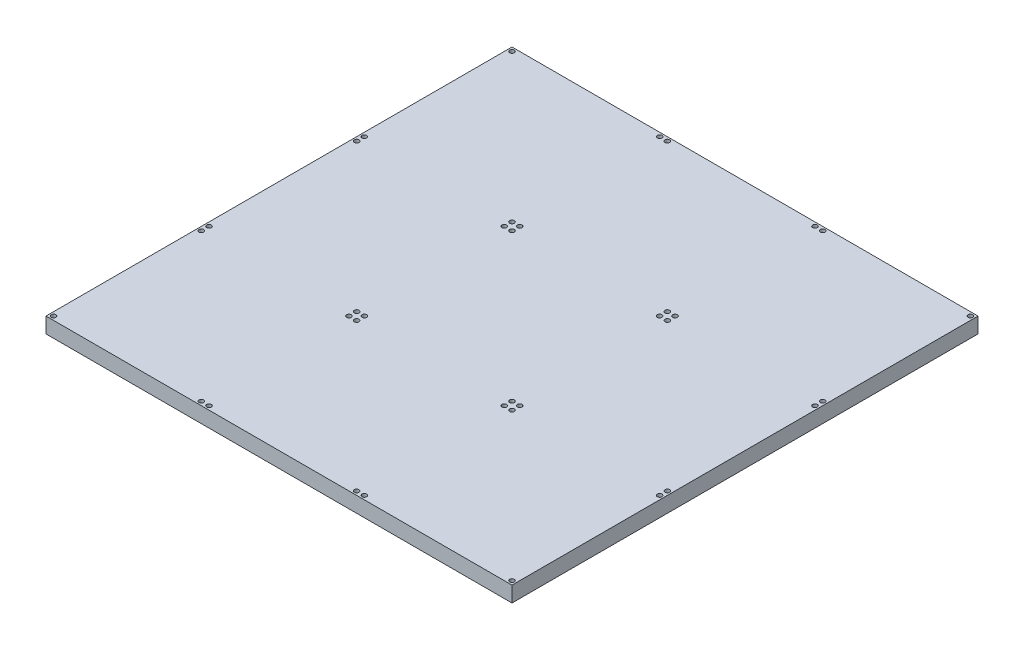
SolidWorks part; units mm, degrees
ref_plane "Front Plane" through (0, 0, 0) normal (0, 0, 1) x (1, 0, 0)
ref_plane "Top Plane" through (0, 0, 0) normal (0, 1, 0) x (1, 0, 0)
ref_plane "Right Plane" through (0, 0, 0) normal (1, 0, 0) x (0, 0, -1)
sketch "Sketch1" plane through (0, 0, 0) normal (0, 1, 0) x (1, 0, 0)
  line L1 (-25.4, -25.4) -> (25.4, -25.4)
  line L2 (-25.4, -25.4) -> (-25.4, 25.4)
  line L3 (-25.4, 25.4) -> (25.4, 25.4)
  line L4 (25.4, -25.4) -> (25.4, 25.4)
  line L5 (-25.4, -25.4) -> (25.4, 25.4) construction
  line L6 (-25.4, 25.4) -> (25.4, -25.4) construction
  point P0 (0, 0)
  dimension "D1" = 50.8
  dimension "D2" = 50.8
extrude "Boss-Extrude1" add sketch "Sketch1" along normal blind 5.08
sketch "Sketch11" plane through (0, 5.08, 0) normal (0, 1, 0) x (1, 0, 0)
  line L5 (-22.86, -22.86) -> (22.86, 22.86) construction
  line L6 (-22.86, 22.86) -> (22.86, -22.86) construction
  line L8 (-25.4, 25.4) -> (-22.86, 22.86) construction
  line L9 (0, -2.794) -> (0, 2.794) construction
  line L10 (-2.794, 0) -> (2.794, 0) construction
  circle A0 centre (-24.1428, 24.1428) radius 0.762
  circle A1 centre (24.1428, 24.1428) radius 0.762
  circle A2 centre (24.1428, -24.1428) radius 0.762
  circle A3 centre (-24.1428, -24.1428) radius 0.762
  point P0 (0, 0)
  dimension "D1" = 1.524
  dimension "D3" = 1.778
extrude "Cut-Extrude6" cut sketch "Sketch11" against normal blind 2.54
pattern_linear "LPattern1" count 3 spacing 50.8 along (0, 0, 1) count 3 spacing 50.8 along (1, 0, 0) of "Boss-Extrude1", "Cut-Extrude6"
